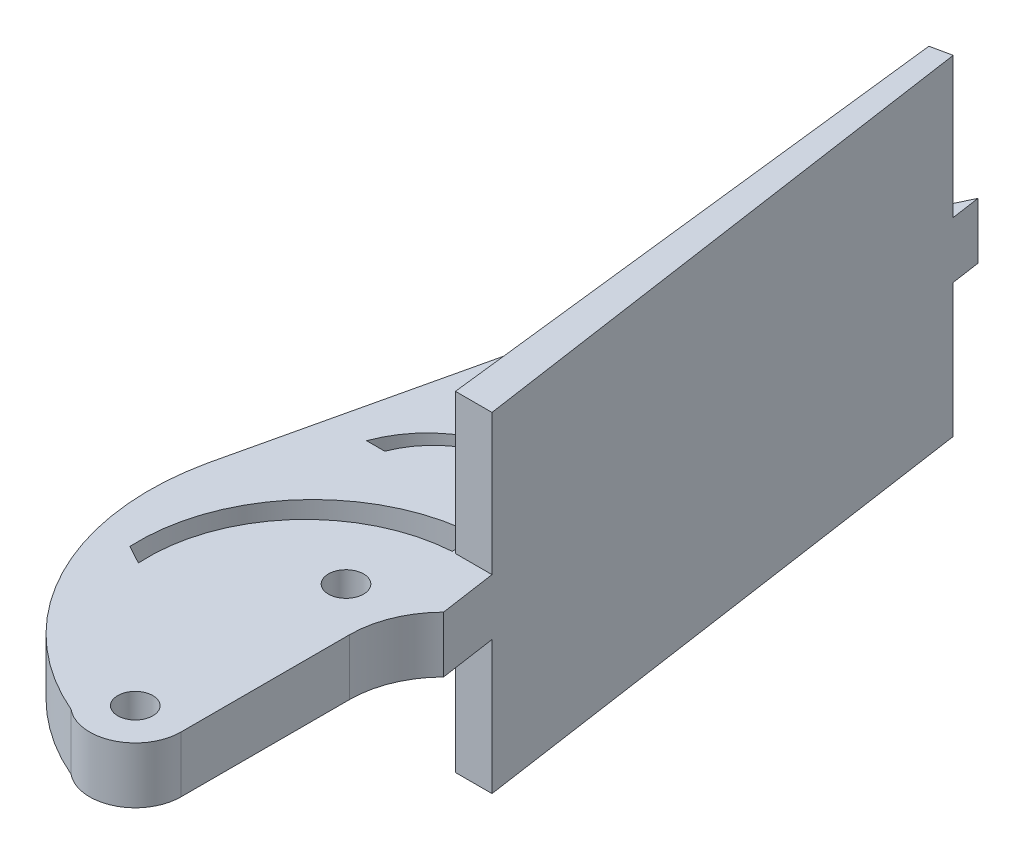
SolidWorks part; units mm, degrees
ref_plane "Alzado" through (0, 0, 0) normal (0, 0, 1) x (1, 0, 0)
ref_plane "Planta" through (0, 0, 0) normal (0, 1, 0) x (1, 0, 0)
ref_plane "Vista lateral" through (0, 0, 0) normal (1, 0, 0) x (0, 0, -1)
sketch "Croquis2" plane through (0, 0, 0) normal (0, 1, 0) x (1, 0, 0)
  line L0 (10.4081, 33.4849) -> (-2.5653, 122.5449)
  line L1 (-6.5, 114.2755) -> (-2.5653, 122.5449)
  line L36 (-6.5, 70) -> (-6.5, 0)
  line L37 (6.5, 0) -> (6.5, 24)
  line L53 (-6.5, 114.2755) -> (-6.5, 70)
  circle A0 centre (0, 0) radius 2.5
  circle A1 centre (0, 30) radius 2.5
  arc A11 (-6.5, 0) -> (6.5, 0) centre (0, 0) ccw
  arc A12 (10.4081, 33.4849) -> (6.5, 24) centre (19.9638, 24) ccw
  dimension "D1" = 6.5
  dimension "D2" = 90
  dimension "D13" = 5
  dimension "D3" = 24
  dimension "D4" = 70
  dimension "D6" = 180
  dimension "D16" = 30
extrude "Saliente-Extruir1" add sketch "Croquis2" along normal blind 8
sketch "Sketch1" plane through (0, 0, 0) normal (0, -1, 0) x (-1, 0, 0)
  line L0 (24.7616, 35.0877) -> (6.5, 114.2755)
  line L1 (6.3785, -1.2508) -> (6.5, 114.2755)
  arc A0 (0, -6.5) -> (24.7616, 35.0877) centre (-9.8718, 27.5432) ccw
  arc A1 (-6.5, 0) -> (6.5, 0) centre (0, 0) ccw construction
  arc A2 (0, -6.5) -> (6.3785, -1.2508) centre (0, 0) ccw
  line M1 (6.5, 0) -> (6.5, 114.2755)
  arc M6 (-6.5, 0) -> (6.5, 0) centre (0, 0) ccw
extrude "Boss-Extrude1" add sketch "Sketch1" against normal blind 8 contours A0 L0 M6 M1
sketch "Sketch2" plane through (0, 0, 0) normal (0, -1, 0) x (-1, 0, 0)
  line L0 (17.3702, 17.8161) -> (20.0229, 19.2514)
  line L1 (-3.5285, 41.5854) -> (-3.5285, 45.3081)
  arc A0 (17.3702, 17.8161) -> (-3.5285, 41.5854) centre (-4.9638, 19.2514) ccw
  arc A1 (20.0229, 19.2514) -> (-3.5285, 45.3081) centre (-4.7811, 20.504) ccw
extrude "Cut-Extrude1" cut sketch "Sketch2" against normal blind 8
sketch "Sketch3" plane through (0, 0, 0) normal (0, -1, 0) x (-1, 0, 0)
  line L0 (13.6172, 49.1339) -> (16.2069, 49.1339)
  line L1 (-2.1153, 56.0509) -> (-2.1153, 57.756)
  arc A0 (16.2069, 49.1339) -> (-2.1153, 57.756) centre (2.7348, 44.2838) ccw
  arc A1 (13.6172, 49.1339) -> (-2.1153, 56.0509) centre (2.2925, 44.7262) ccw
extrude "Cut-Extrude2" cut sketch "Sketch3" against normal blind 8
sketch "Sketch4" plane through (0, 0, 0) normal (0, -1, 0) x (-1, 0, 0)
  line L0 (11.3676, 69.8935) -> (13.0755, 70.7722)
  line L1 (0, 76.0415) -> (0, 79.4107)
  arc A0 (11.3676, 69.8935) -> (0, 76.0415) centre (2.6098, 67.2837) ccw
  arc A1 (13.0755, 70.7722) -> (0, 79.4107) centre (2.2185, 68.5537) ccw
extrude "Cut-Extrude3" cut sketch "Sketch4" against normal blind 8
sketch "Sketch5" plane through (0, 0, 0) normal (0, -1, 0) x (-1, 0, 0)
  line L0 (-9.2332, 41.5507) -> (1.963, 118.4102)
  line L1 (-10.4081, 33.4849) -> (2.5653, 122.5449) construction
  line L2 (-9.2332, 41.5507) -> (-4.0326, 41.5507)
  line L3 (-4.0326, 41.5507) -> (4.8194, 117.8075)
  line L4 (2.5653, 122.5449) -> (6.5, 114.2755) construction
  line L5 (4.8194, 117.8075) -> (1.963, 118.4102)
  point P4 (-3.9716, 42.0224)
  point P9 (-9.2332, 41.5507)
  point P10 (4.8194, 118.4102)
extrude "Boss-Extrude2" add sketch "Sketch5" along normal blind 19 and the other way blind 28
